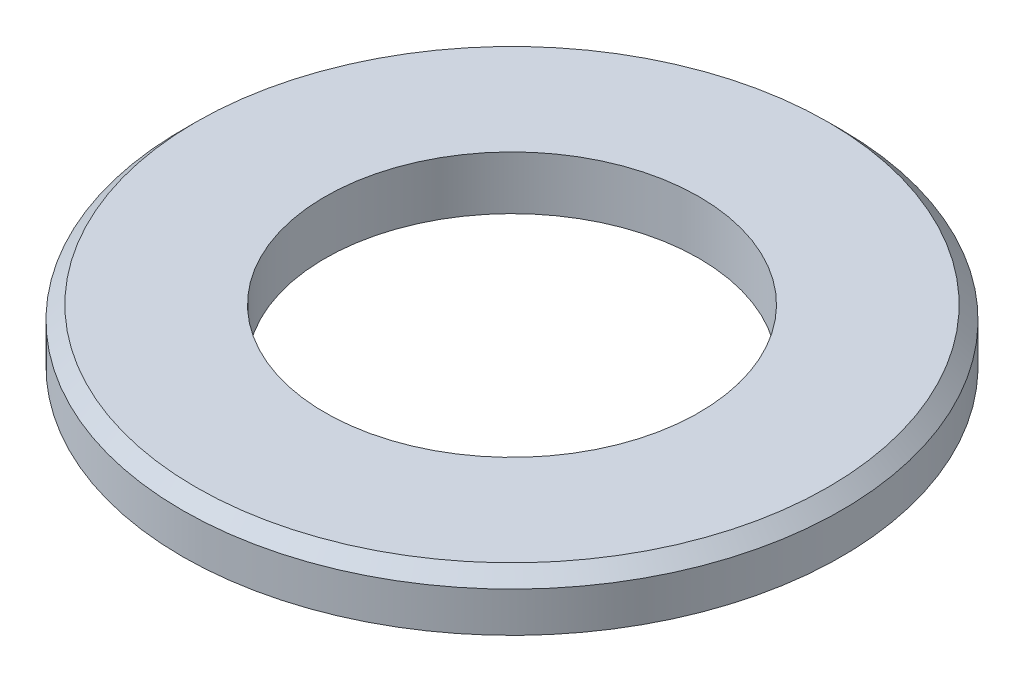
SolidWorks part; units mm, degrees
ref_plane "基准面1" through (0, 0, 0) normal (0, 0, 1) x (1, 0, 0)
ref_plane "基准面2" through (0, 0, 0) normal (0, 1, 0) x (1, 0, 0)
ref_plane "基准面3" through (0, 0, 0) normal (1, 0, 0) x (0, 0, -1)
sketch "尺寸草图" plane through (0, 0, 0) normal (0, 0, 1) x (1, 0, 0)
  line L0 (0, 0) -> (9.1, 0)
  point P3 (3, 0)
  point P4 (37, 0)
  point P5 (21, 0)
  dimension "h" = 3
  dimension "d2" = 37
  dimension "d1" = 21
sketch "草图1" plane through (0, 0, 0) normal (0, 0, 1) x (1, 0, 0)
  line L0 (0, 0) -> (0, 52.7318) construction
  line L1 (-17.75, 11.6445) -> (-18.5, 10.8945)
  line L2 (-10.5, 8.6445) -> (-18.5, 8.6445)
  line L3 (-10.5, 8.6445) -> (-10.5, 11.6445)
  line L4 (-10.5, 11.6445) -> (-17.75, 11.6445)
  line L5 (-18.5, 8.6445) -> (-18.5, 10.8945)
  point P4 (-18.5, 11.6445)
  dimension "h" = 3
  dimension "D1" = 10.5
  dimension "D2" = 18.5
revolve "基体-旋转" add sketch "草图1" angle 360 about L0
equation "\"h@草图1\" = \"h@尺寸草图\""
equation "\"D1@草图1\" = \"d1@尺寸草图\" / 2"
equation "\"D2@草图1\" = \"d2@尺寸草图\" / 2"
equation "\"D5@草图1\" = \"h@草图1\" *0.25"
